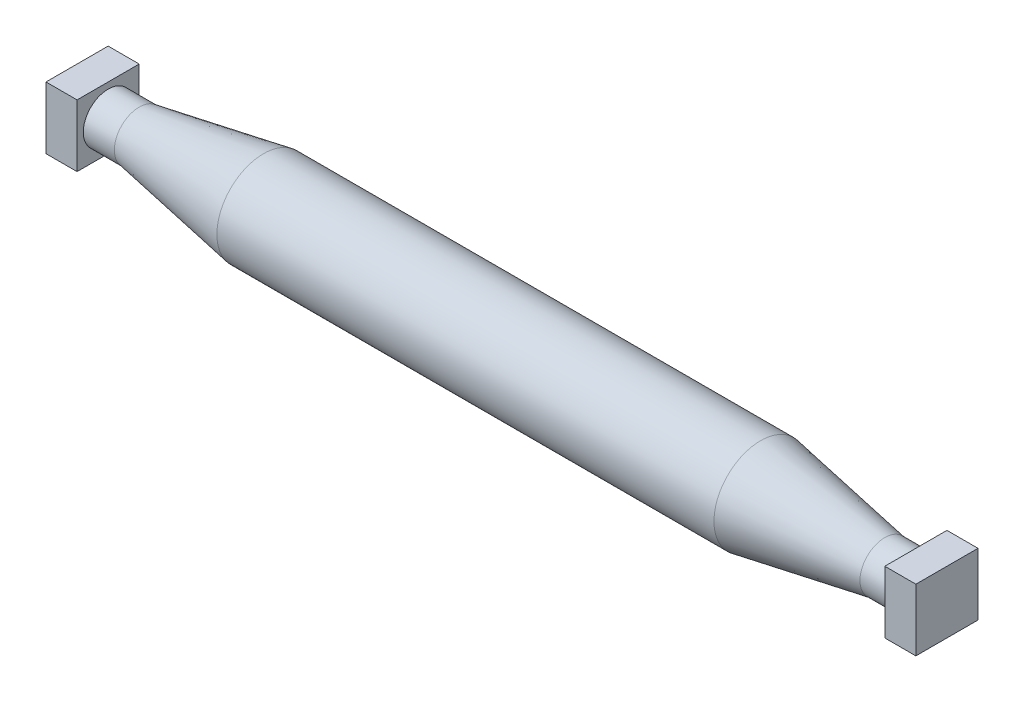
SolidWorks part; units mm, degrees
ref_plane "Front Plane" through (0, 0, 0) normal (0, 0, 1) x (1, 0, 0)
ref_plane "Top Plane" through (0, 0, 0) normal (0, 1, 0) x (1, 0, 0)
ref_plane "Right Plane" through (0, 0, 0) normal (1, 0, 0) x (0, 0, -1)
sketch "Sketch1" plane through (0, 0, 0) normal (0, 0, 1) x (1, 0, 0)
  line L0 (0, 0) -> (177.8, 0) construction
  line L1 (0, 19.05) -> (101.6, 19.05)
  line L2 (0, 0) -> (165.1, 0)
  line L4 (101.6, 19.05) -> (152.4, 10.16)
  line L5 (152.4, 10.16) -> (152.4, 0)
  line L7 (152.4, 10.16) -> (165.1, 10.16)
  line L8 (165.1, 10.16) -> (165.1, 0)
  line L10 (-0.7371, 0) -> (297.7401, 0) construction
  line L11 (0, 19.05) -> (0, 0)
  dimension "D1" = 19.05
  dimension "D2" = 10.16
  dimension "D3" = 12.7
  dimension "D4" = 101.6
  dimension "D5" = 165.1
  dimension "D7" = 12.7
revolve "Revolve3" add sketch "Sketch1" angle 360 about L2
sketch "Sketch3" plane through (165.1, 0, 0) normal (1, 0, 0) x (0, 0, -1)
  line L1 (-12.7, -12.7) -> (12.7, -12.7)
  line L2 (-12.7, -12.7) -> (-12.7, 12.7)
  line L3 (-12.7, 12.7) -> (12.7, 12.7)
  line L4 (12.7, -12.7) -> (12.7, 12.7)
  line L5 (-12.7, -12.7) -> (12.7, 12.7) construction
  line L6 (-12.7, 12.7) -> (12.7, -12.7) construction
  point P0 (0, 0)
  dimension "D1" = 25.4
  dimension "D2" = 25.4
extrude "Boss-Extrude2" add sketch "Sketch3" along normal blind 12.7
mirror "Mirror1" about plane through (0, 0, 0) normal (1, 0, 0) of bodies 104 102
